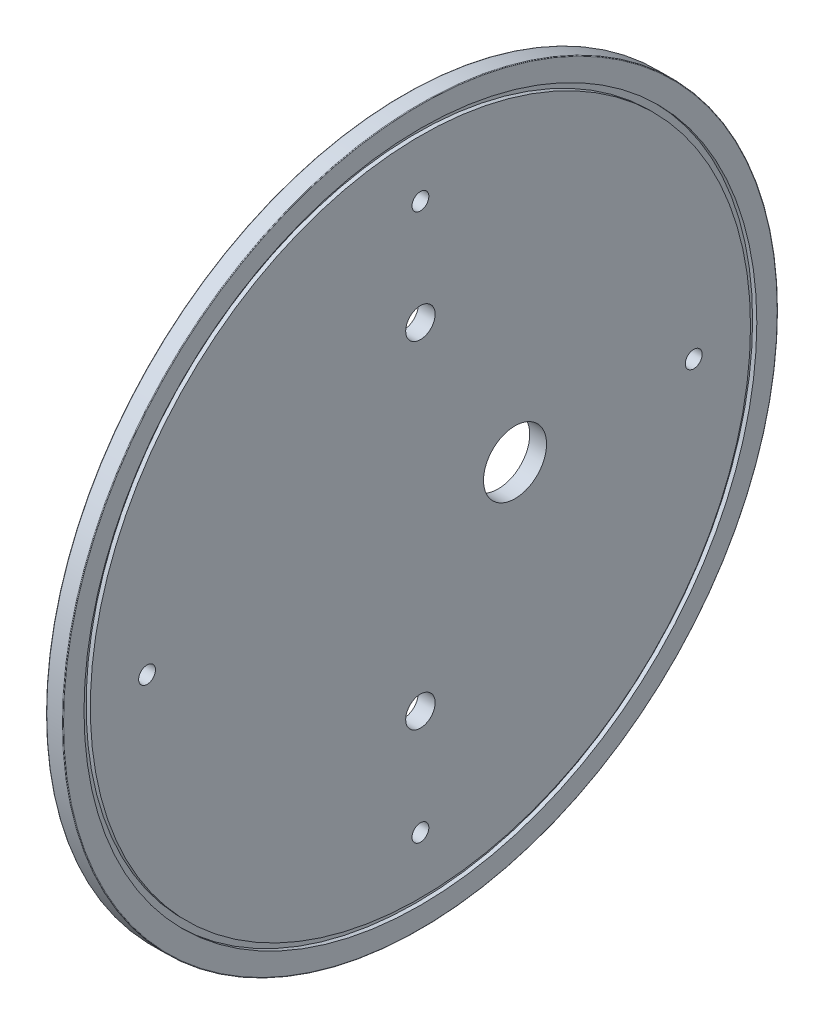
SolidWorks part; units mm, degrees
material "1060 合金"
ref_plane "前视基准面" through (0, 0, 0) normal (0, 0, 1) x (1, 0, 0)
ref_plane "上视基准面" through (0, 0, 0) normal (0, 1, 0) x (1, 0, 0)
ref_plane "右视基准面" through (0, 0, 0) normal (1, 0, 0) x (0, 0, -1)
sketch "草图1" plane through (0, 0, 0) normal (1, 0, 0) x (0, 0, -1)
  circle A0 centre (0, 0) radius 170
extrude "凸台-拉伸1" add sketch "草图1" along normal blind 8
sketch "草图5" plane through (8, 0, 0) normal (1, 0, 0) x (0, 0, -1)
  circle A0 centre (0, 130) radius 4
extrude "切除-拉伸4" cut sketch "草图5" against normal blind 10
pattern_circular "阵列(圆周)3" count 4 over 360 about axis through (0, 0, 0) along (1, 0, 0) of "切除-拉伸4"
sketch "草图7" plane through (8, 0, 0) normal (1, 0, 0) x (0, 0, -1)
  circle A0 centre (0, 0) radius 157
  circle A1 centre (0, 0) radius 160
extrude "切除-拉伸5" cut sketch "草图7" against normal blind 2
fillet "圆角1" radius 0.3 2 edges at (0, 0, -170) (8, 0, -170)
sketch "草图8" plane through (8, 0, 0) normal (1, 0, 0) x (0, 0, -1)
  circle A0 centre (45, 0) radius 15
extrude "切除-拉伸6" cut sketch "草图8" against normal blind 10
sketch "草图10" plane through (0, 0, 0) normal (-1, 0, 0) x (0, 0, 1)
  circle A0 centre (0, -80) radius 7
  circle A1 centre (0, 80) radius 7
extrude "切除-拉伸7" cut sketch "草图10" against normal blind 10
